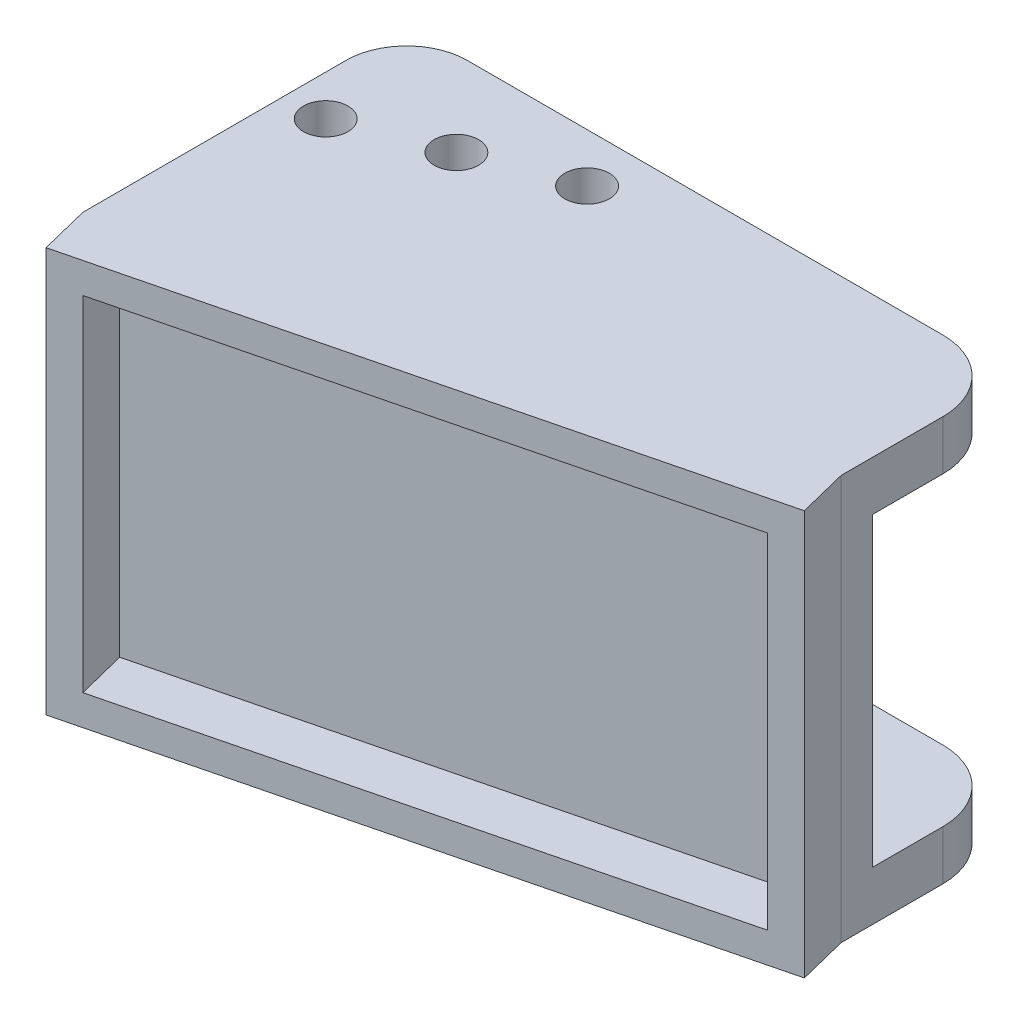
SolidWorks part; units mm, degrees
ref_plane "前视基准面" through (0, 0, 0) normal (0, 0, 1) x (1, 0, 0)
ref_plane "上视基准面" through (0, 0, 0) normal (0, 1, 0) x (1, 0, 0)
ref_plane "右视基准面" through (0, 0, 0) normal (1, 0, 0) x (0, 0, -1)
other "Configuration Table"
sketch "草图1" plane through (0, 0, 0) normal (0, 1, 0) x (1, 0, 0)
  line L0 (-15, -8) -> (15, -0.5202)
  line L1 (-15, 8) -> (15, 8)
  line L2 (-15, 8) -> (-15, -8)
  line L3 (-15, -8) -> (15, -8) construction
  line L4 (15, 8) -> (15, -8) construction
  line L5 (-15, 8) -> (15, -8) construction
  line L6 (-15, -8) -> (15, 8) construction
  line L7 (15, 8) -> (15, -0.5202)
  point P0 (0, 0)
  dimension "D1" = 14
  dimension "D2" = 16
  dimension "D3" = 30
extrude "凸台-拉伸1" add sketch "草图1" along normal blind 20
sketch "草图2" plane through (0, 20, 0) normal (0, 1, 0) x (1, 0, 0)
  line L0 (-15, 8) -> (-15, -8) construction
  line L1 (-13, 2) -> (-1.5285, 6.4035) construction
  line L4 (-12.5, 2) -> (-1.0308, 2) construction
  line L5 (15, 8) -> (-15, 8) construction
  circle A1 centre (-13, 2) radius 1.1
  circle A2 centre (-8.3321, 3.7918) radius 1.1
  circle A3 centre (-3.6642, 5.5837) radius 1.1
  dimension "D3" = 21
  dimension "D5" = 5
  dimension "D1" = 10
  dimension "D4" = 5
  dimension "D2" = 2
sketch "草图3" plane through (0, 0, -8) normal (0, 0, -1) x (-1, 0, 0)
  line L0 (-15, 10) -> (15, 10) construction
  line L1 (-15, 20) -> (-15, 0) construction
  line L2 (15, 20) -> (15, 0) construction
  line L3 (-15, 17.55) -> (15, 17.55)
  line L4 (-15, 2.45) -> (15, 2.45)
  line L5 (-15, 17.55) -> (-15, 2.45)
  line L6 (15, 17.55) -> (15, 2.45)
  dimension "D1" = 7.55
  dimension "D2" = 7.55
extrude "切除-拉伸2" cut sketch "草图2" against normal through all
ref_plane "基准面1" through (0.6371, 0, 2.5553) normal (0.2419, 0, 0.9703) x (0.9703, 0, -0.2419)
extrude "切除-拉伸3" cut sketch "草图3" against normal up to surface (14.4541 mm away) up to plane "基准面1"
fillet "圆角1" radius 3 2 edges at (-15, 1.225, -8) (-15, 18.775, -8)
sketch "草图6" plane through (1, 0, 4.0108) normal (0.2419, 0, 0.9703) x (0.9703, 0, -0.2419)
  line L0 (-14.9898, 18.5) -> (-14.9898, 1.5)
  line L1 (-14.9898, 1.5) -> (12.9286, 1.5)
  line L2 (12.9286, 1.5) -> (12.9286, 18.5)
  line L3 (12.9286, 18.5) -> (-14.9898, 18.5)
  line L4 (-16.4898, 20) -> (-16.4898, 0) construction
  line L5 (14.4286, 20) -> (14.4286, 0) construction
  line L6 (-16.4898, 20) -> (14.4286, 20) construction
  line L7 (-16.4898, 0) -> (14.4286, 0) construction
  line L9 (-16.4898, 20) -> (14.4286, 20)
  line L10 (-16.4898, 20) -> (-16.4898, 0)
  line L11 (-16.4898, 0) -> (14.4286, 0)
  line L12 (14.4286, 20) -> (14.4286, 0)
  dimension "D1" = 1.5
  dimension "D2" = 1.5
  dimension "D3" = 1.5
  dimension "D4" = 1.5
extrude "凸台-拉伸2" add sketch "草图6" along normal blind 2.5
fillet "圆角2" radius 3.5 2 edges at (15, 1.225, -8) (15, 18.775, -8)
